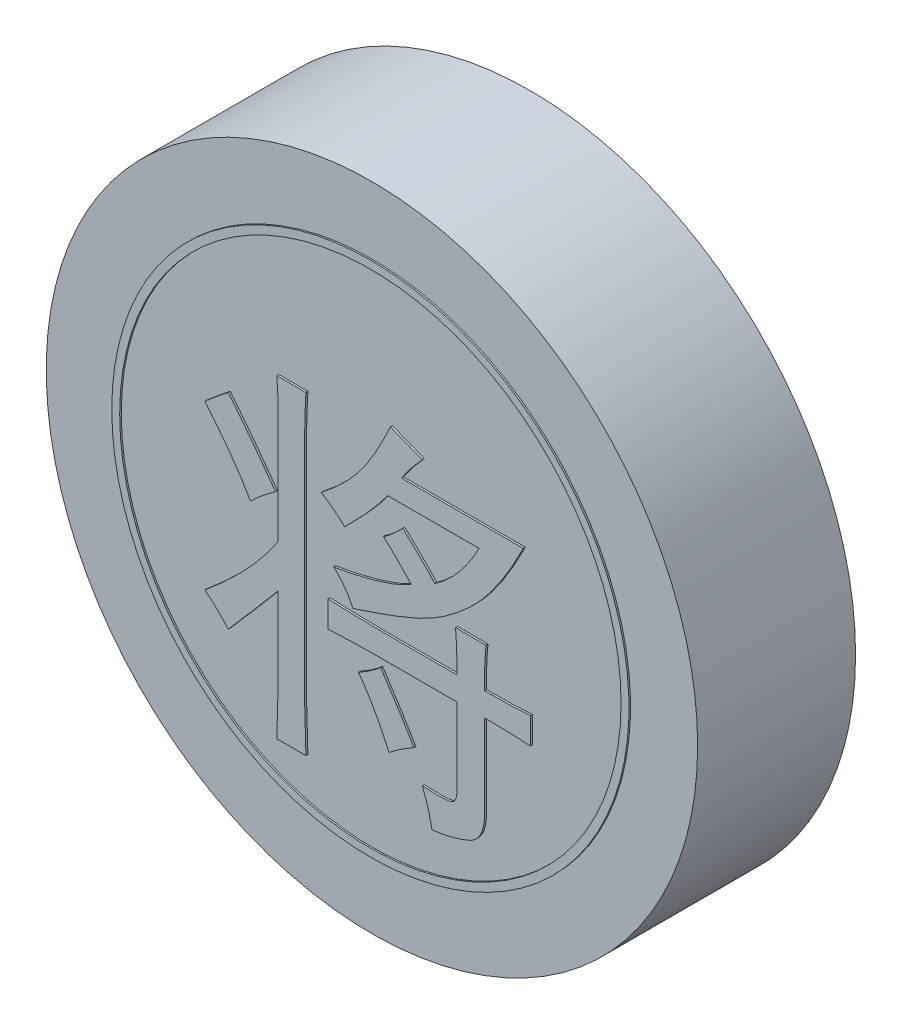
SolidWorks part; units mm, degrees
ref_plane "前视基准面" through (0, 0, 0) normal (0, 0, 1) x (1, 0, 0)
ref_plane "上视基准面" through (0, 0, 0) normal (0, 1, 0) x (1, 0, 0)
ref_plane "右视基准面" through (0, 0, 0) normal (1, 0, 0) x (0, 0, -1)
other "Configuration Table"
sketch "草图1" plane through (0, 0, 0) normal (0, 0, 1) x (1, 0, 0)
  circle A0 centre (0, 0) radius 16.5
  dimension "D1" = 33
extrude "Diameter33_Height8" add sketch "草图1" against normal blind 8
sketch "草图2" plane through (0, 0, 0) normal (0, 0, 1) x (1, 0, 0)
  text T0 "将" font "SimHei" height 12
extrude "Character_将" add sketch "草图2" along normal blind 0.1
sketch "草图3" plane through (0, 0, 0) normal (0, 0, 1) x (1, 0, 0)
  circle A0 centre (0, 0) radius 13.1
  circle A1 centre (0, 0) radius 12.7
extrude "Ink_ring" add sketch "草图3" along normal blind 0.08
